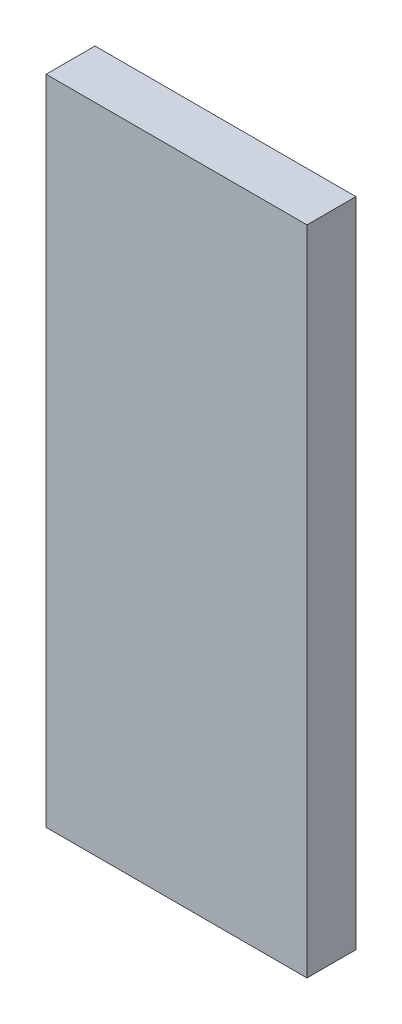
SolidWorks part; units mm, degrees
material "Acrylic (Medium-high impact)"
ref_plane "Front Plane" through (0, 0, 0) normal (0, 0, 1) x (1, 0, 0)
ref_plane "Top Plane" through (0, 0, 0) normal (0, 1, 0) x (1, 0, 0)
ref_plane "Right Plane" through (0, 0, 0) normal (1, 0, 0) x (0, 0, -1)
sketch "Sketch1" plane through (0, 0, 0) normal (0, 0, 1) x (1, 0, 0)
  line L0 (12, 0) -> (-12, 0)
  line L1 (55, 0) -> (-55, 0) construction
  line L2 (-12, 0) -> (-12, 60)
  line L3 (-12, 60) -> (0, 60)
  line L6 (0, -55) -> (0, 55) construction
  line L8 (12, 60) -> (0, 60)
  line L9 (12, 0) -> (12, 60)
  point P0 (0, 60)
  point P12 (0, 66)
  point P15 (0, 0)
  dimension "D1" = 12
  dimension "D4" = 60
extrude "Boss-Extrude1" add sketch "Sketch1" along normal blind 4.5
